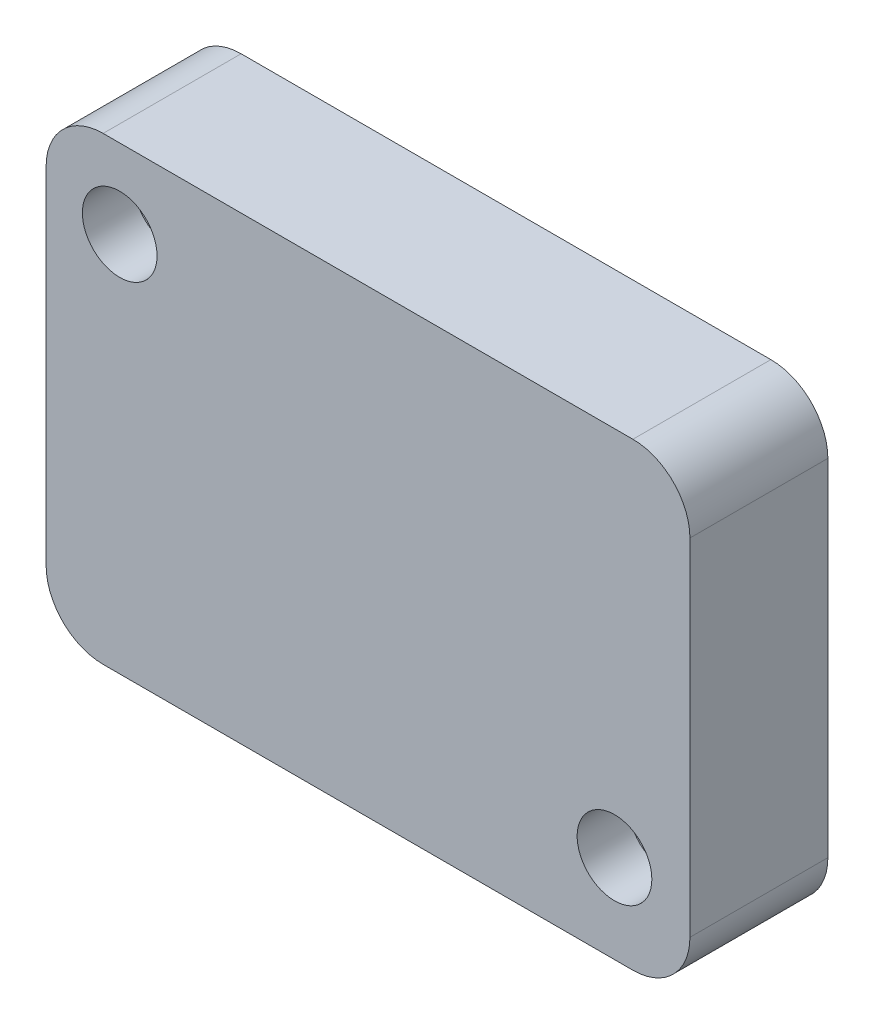
SolidWorks part; units mm, degrees
ref_plane "Top" through (0, 0, 0) normal (0, 0, 1) x (1, 0, 0)
ref_plane "Front_Back" through (0, 0, 0) normal (0, 1, 0) x (1, 0, 0)
ref_plane "Right_Left" through (0, 0, 0) normal (1, 0, 0) x (0, 0, -1)
other "Configuration Table"
sketch "Sketch1" plane through (0, 0, 0) normal (0, 0, 1) x (1, 0, 0)
  line L1 (-81.026, 63.5) -> (-7.874, 63.5)
  line L2 (-88.9, 55.626) -> (-88.9, 7.874)
  line L3 (-81.026, 0) -> (-7.874, 0)
  line L4 (0, 55.626) -> (0, 7.874)
  arc A0 (-81.026, 63.5) -> (-88.9, 55.626) centre (-81.026, 55.626) ccw
  arc A1 (-88.9, 7.874) -> (-81.026, 0) centre (-81.026, 7.874) ccw
  arc A2 (-7.874, 0) -> (0, 7.874) centre (-7.874, 7.874) ccw
  arc A3 (-7.874, 63.5) -> (0, 55.626) centre (-7.874, 55.626) cw
  point P6 (-88.9, 63.5)
  point P11 (0, 0)
  point P14 (0, 63.5)
  dimension "D3" = 7.874
  dimension "Depth" = 63.5
  dimension "Width" = 88.9
extrude "Die" add sketch "Sketch1" along normal blind 19.05
hole_wizard "Drill&CBore For 1/4 SHCS (Shallow)1" positions "Sketch3" profile "Sketch2" counterbore size "1/4" standard "MT&D Inch Mounting" end condition through all
sketch "Sketch3" plane through (0, 0, 19.05) normal (0, 0, 1) x (1, 0, 0)
  line L0 (-7.874, 63.5) -> (-81.026, 63.5) construction
  line L1 (-88.9, 55.626) -> (-88.9, 7.874) construction
  line L2 (0, 7.874) -> (0, 55.626) construction
  line L3 (-81.026, 0) -> (-7.874, 0) construction
  point P0 (-10.414, 12.192)
  point P1 (-78.74, 52.578)
  dimension "D1" = 10.922
  dimension "D2" = 10.16
  dimension "D3" = 10.414
  dimension "D4" = 12.192
sketch "Sketch2" plane through (-10.414, 12.192, 19.05) normal (1, 0, 0) x (0, -1, 0)
  line L0 (0, 0) -> (0, 19.05)
  line L1 (0, 19.05) -> (3.5687, 19.05)
  line L2 (4.318, 19.05) -> (-43.434, 19.05) construction
  line L3 (3.5687, 19.05) -> (3.5687, 7.112)
  line L4 (3.5687, 7.112) -> (5.1562, 7.112)
  line L5 (5.1562, 7.112) -> (5.1562, 0)
  line L7 (5.1562, 0) -> (0, 0)
  line L11 (0, -6.35) -> (0, 19.05) construction
  dimension "Thru Hole Dia." = 7.1374
  dimension "Thru Hole Depth" = 19.05
  dimension "C'Bore Dia." = 10.3124
  dimension "C'Bore Depth" = 7.112
